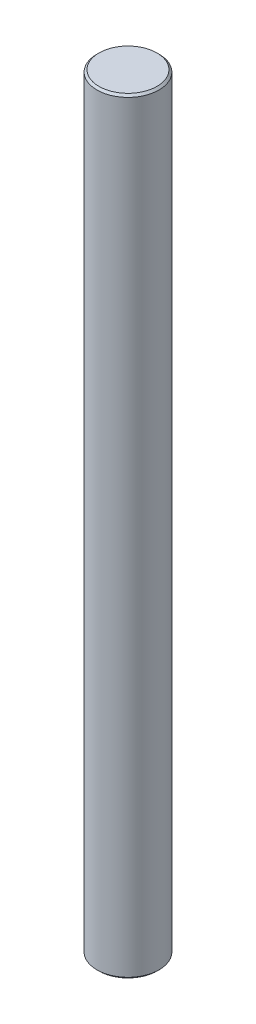
SolidWorks part; units mm, degrees
material "Alloy Steel"
ref_plane "Front Plane" through (0, 0, 0) normal (0, 0, 1) x (1, 0, 0)
ref_plane "Top Plane" through (0, 0, 0) normal (0, 1, 0) x (1, 0, 0)
ref_plane "Right Plane" through (0, 0, 0) normal (1, 0, 0) x (0, 0, -1)
sketch "Sketch1" plane through (0, 0, 0) normal (0, 1, 0) x (1, 0, 0)
  circle A0 centre (0, 0) radius 1.5
  dimension "D1" = 3
extrude "Boss-Extrude1" add sketch "Sketch1" along normal blind 37
chamfer "Chamfer1" distance 0.1 2 edges at (0, 0, 1.5) (0, 37, 1.5)
